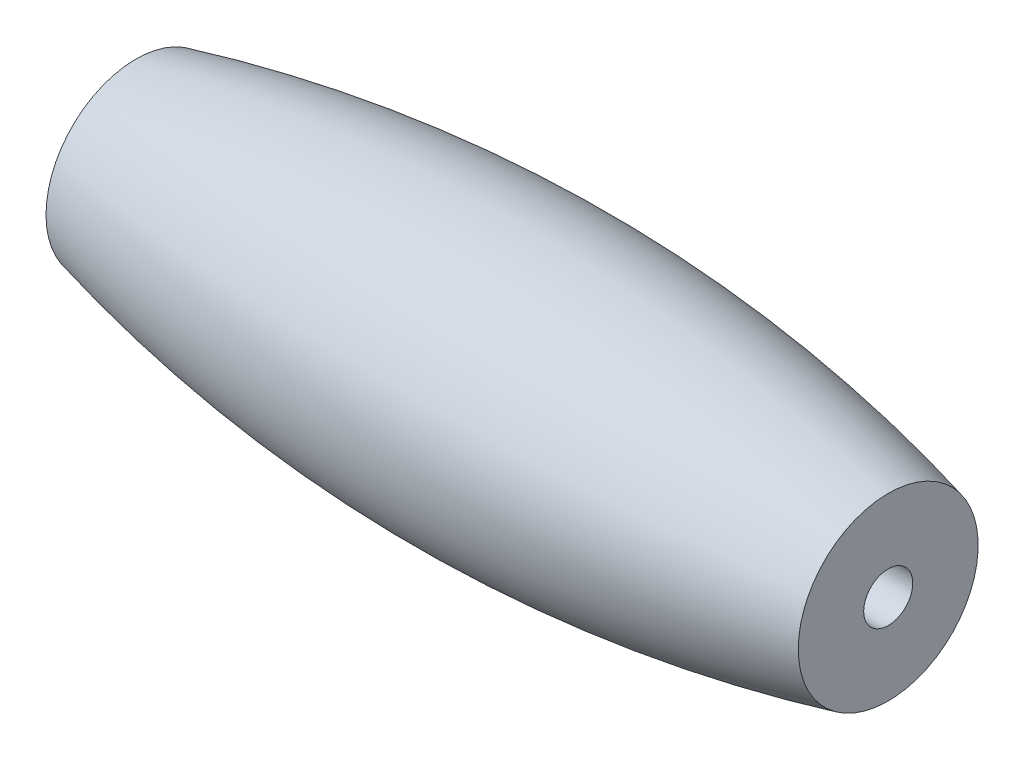
SolidWorks part; units mm, degrees
ref_plane "Ön Düzlem" through (0, 0, 0) normal (0, 0, 1) x (1, 0, 0)
ref_plane "Üst Düzlem" through (0, 0, 0) normal (0, 1, 0) x (1, 0, 0)
ref_plane "Sağ Düzlem" through (0, 0, 0) normal (1, 0, 0) x (0, 0, -1)
sketch "Çizim10" plane through (0, 0, 0) normal (0, 0, 1) x (1, 0, 0)
  line L0 (0, 0) -> (0, 11)
  line L1 (0, 11) -> (92, 11)
  line L2 (92, 11) -> (92, 0)
  arc A1 (92, 0) -> (0, 0) centre (46, 184.3475) cw
  dimension "D1" = 11
  dimension "D2" = 92
revolve "Döndür21" add sketch "Çizim10" angle 360 about L1
sketch "Çizim13" plane through (0, 0, 0) normal (-1, 0, 0) x (0, 0, 1)
  line L0 (0, 22) -> (0, 0) construction
  circle A0 centre (0, 11) radius 11 construction
  circle A1 centre (0, 11) radius 3
extrude "Kes-Ekstrüzyon7" cut sketch "Çizim13" against normal blind 100
